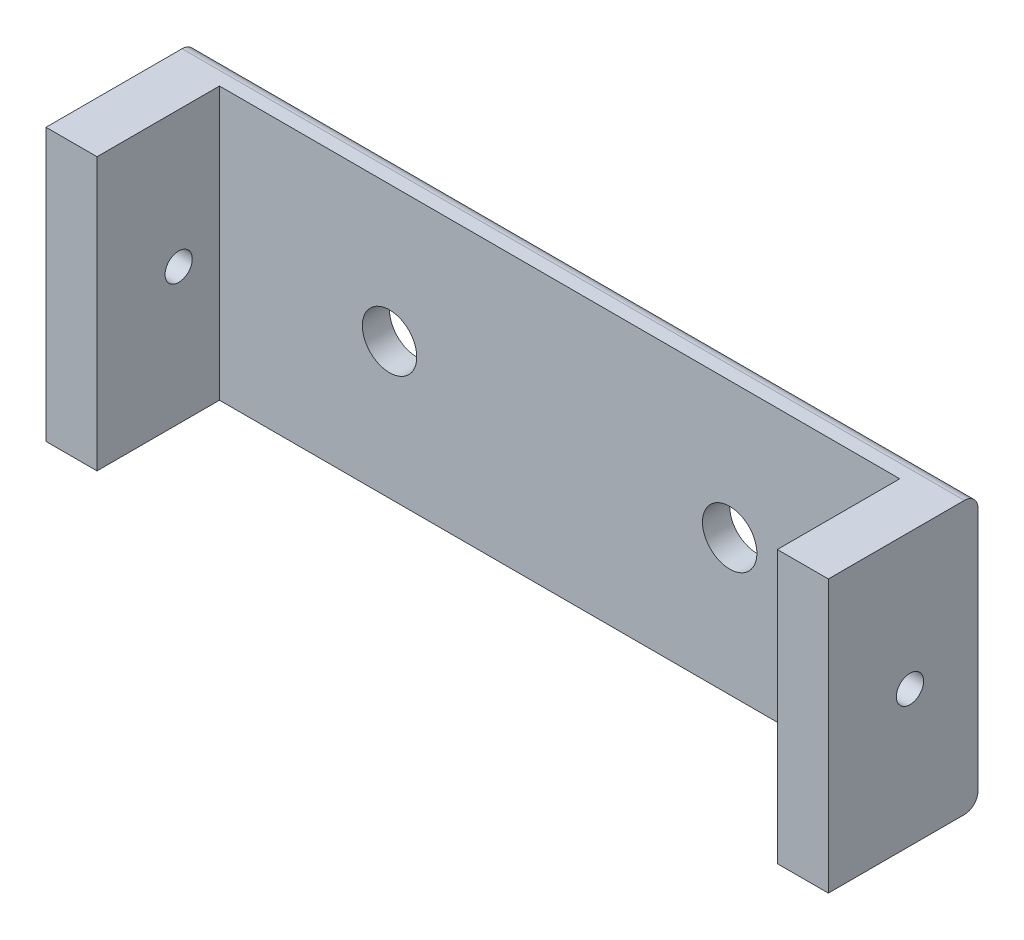
SolidWorks part; units mm, degrees
ref_plane "前视基准面" through (0, 0, 0) normal (0, 0, 1) x (1, 0, 0)
ref_plane "上视基准面" through (0, 0, 0) normal (0, 1, 0) x (1, 0, 0)
ref_plane "右视基准面" through (0, 0, 0) normal (1, 0, 0) x (0, 0, -1)
other "Configuration Table"
sketch "草图2" plane through (0, 0, 0) normal (0, 0, 1) x (1, 0, 0)
  line L1 (-57.5, -20) -> (57.5, -20)
  line L2 (-57.5, -20) -> (-57.5, 20)
  line L3 (-57.5, 20) -> (57.5, 20)
  line L4 (57.5, -20) -> (57.5, 20)
  line L5 (-57.5, -20) -> (57.5, 20) construction
  line L6 (-57.5, 20) -> (57.5, -20) construction
  point P0 (0, 0)
  dimension "D1" = 115
  dimension "D2" = 40
extrude "凸台-拉伸1" add sketch "草图2" along normal blind 25
sketch3d "3D草图1"
  point P0 (1.5972, -4.6015, 25)
ref_plane "基准面1" through (0, 0, 25) normal (0, 0, 1) x (1, 0, 0)
sketch "草图3" plane through (0, 0, 25) normal (0, 0, 1) x (1, 0, 0)
  line L0 (57.5, 20) -> (-57.5, 20) construction
  line L1 (-50, -20) -> (50, -20)
  line L2 (-50, -20) -> (-50, 20)
  line L3 (-50, 20) -> (50, 20)
  line L4 (50, -20) -> (50, 20)
  line L5 (-50, -20) -> (50, 20) construction
  line L6 (-50, 20) -> (50, -20) construction
  point P0 (0, 0)
  dimension "D1" = 100
extrude "切除-拉伸1" cut sketch "草图3" against normal blind 21
sketch3d "3D草图2"
  point P0 (-57.5, 12.0338, 9.7326)
ref_plane "基准面2" through (-57.5, 0, 0) normal (-1, 0, 0) x (0, 0, 1)
sketch "草图5" plane through (-57.5, 0, 0) normal (-1, 0, 0) x (0, 0, 1)
  line L0 (25, -20) -> (0, -20) construction
  line L1 (0, 20) -> (20, 20) construction
  line L2 (0, 20) -> (0, -20) construction
  line L3 (0, -20) -> (20, -20) construction
  line L4 (20, 20) -> (20, -20) construction
  line L5 (0, 20) -> (20, -20) construction
  line L6 (0, -20) -> (20, 20) construction
  circle A0 centre (10, 0) radius 2
  point P4 (10, 0)
  dimension "D1" = 20
extrude "切除-拉伸2" cut sketch "草图5" against normal blind 138
fillet "圆角1" radius 2 1 edges at (0, 20, 0)
fillet "圆角2" radius 2 1 edges at (0, -20, 0)
sketch3d "3D草图3"
  point P0 (-32.7808, 15.6941, 4)
ref_plane "基准面3" through (0, 0, 4) normal (0, 0, 1) x (1, 0, 0)
sketch "草图6" plane through (0, 0, 4) normal (0, 0, 1) x (1, 0, 0)
  line L0 (-50, -20) -> (50, -20) construction
  line L1 (-25, 20) -> (25, 20) construction
  line L2 (-25, 20) -> (-25, -20) construction
  line L3 (-25, -20) -> (25, -20) construction
  line L4 (25, 20) -> (25, -20) construction
  line L5 (-25, 20) -> (25, -20) construction
  line L6 (-25, -20) -> (25, 20) construction
  line L7 (0, -20) -> (0, 20) construction
  circle A0 centre (-25, 0) radius 4
  circle A1 centre (25, 0) radius 4
  point P0 (0, 0)
  point P13 (0, 0)
  dimension "D1" = 50
extrude "切除-拉伸3" cut sketch "草图6" against normal blind 9
sketch3d "3D草图4"
  point P0 (-52.7536, -9.5449, 25)
ref_plane "基准面4" through (0, 0, 25) normal (0, 0, 1) x (1, 0, 0)
sketch "草图7" plane through (0, 0, 25) normal (0, 0, 1) x (1, 0, 0)
  line L1 (-57.5, 20) -> (57.5, 20)
  line L2 (-57.5, 20) -> (-57.5, -20)
  line L3 (-57.5, -20) -> (57.5, -20)
  line L4 (57.5, 20) -> (57.5, -20)
  line L5 (-57.5, 20) -> (57.5, -20) construction
  line L6 (-57.5, -20) -> (57.5, 20) construction
  point P4 (0, 0)
extrude "切除-拉伸4" cut sketch "草图7" against normal blind 3
